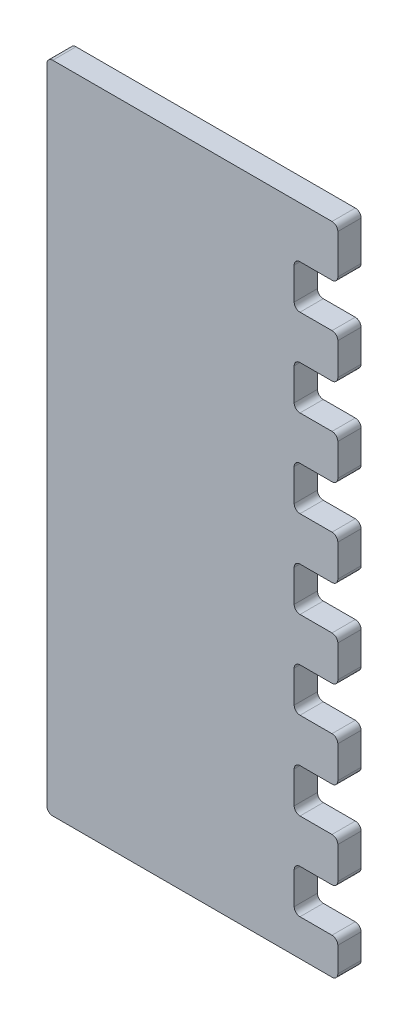
SolidWorks part; units mm, degrees
ref_plane "Front Plane" through (0, 0, 0) normal (0, 0, 1) x (1, 0, 0)
ref_plane "Top Plane" through (0, 0, 0) normal (0, 1, 0) x (1, 0, 0)
ref_plane "Right Plane" through (0, 0, 0) normal (1, 0, 0) x (0, 0, -1)
sketch "Sketch1" plane through (0, 0, 0) normal (0, 0, 1) x (1, 0, 0)
  line L1 (-100, 0) -> (100, 0)
  line L2 (-100, 0) -> (-100, 450)
  line L3 (-100, 450) -> (100, 450)
  line L4 (100, 0) -> (100, 450)
  point P4 (0, 0)
  dimension "D1" = 200
  dimension "D2" = 450
extrude "Boss-Extrude1" add sketch "Sketch1" along normal blind 16
sketch "Sketch2" plane through (0, 0, 16) normal (0, 0, 1) x (1, 0, 0)
  line L0 (100, 0) -> (100, 25)
  line L1 (100, 0) -> (100, 450) construction
  line L2 (100, 25) -> (70, 25)
  line L3 (70, 25) -> (70, 55)
  line L4 (70, 55) -> (100, 55)
  line L5 (70, 110) -> (100, 110)
  line L6 (70, 80) -> (70, 110)
  line L7 (100, 80) -> (70, 80)
  line L8 (100, 55) -> (100, 80)
  line L9 (70, 165) -> (100, 165)
  line L10 (70, 135) -> (70, 165)
  line L11 (100, 135) -> (70, 135)
  line L12 (100, 110) -> (100, 135)
  line L13 (70, 220) -> (100, 220)
  line L14 (70, 190) -> (70, 220)
  line L15 (100, 190) -> (70, 190)
  line L16 (100, 165) -> (100, 190)
  line L17 (70, 275) -> (100, 275)
  line L18 (70, 245) -> (70, 275)
  line L19 (100, 245) -> (70, 245)
  line L20 (100, 220) -> (100, 245)
  line L21 (70, 330) -> (100, 330)
  line L22 (70, 300) -> (70, 330)
  line L23 (100, 300) -> (70, 300)
  line L24 (100, 275) -> (100, 300)
  line L25 (70, 385) -> (100, 385)
  line L26 (70, 355) -> (70, 385)
  line L27 (100, 355) -> (70, 355)
  line L28 (100, 330) -> (100, 355)
  line L29 (70, 440) -> (100, 440)
  line L30 (70, 410) -> (70, 440)
  line L31 (100, 410) -> (70, 410)
  line L32 (100, 385) -> (100, 410)
  line L33 (70, 495) -> (100, 495)
  line L34 (70, 465) -> (70, 495)
  line L35 (100, 465) -> (70, 465)
  line L36 (100, 440) -> (100, 465)
  line L37 (70, 550) -> (100, 550)
  line L38 (70, 520) -> (70, 550)
  line L39 (100, 520) -> (70, 520)
  line L40 (100, 495) -> (100, 520)
  line L41 (70, 605) -> (100, 605)
  line L42 (70, 575) -> (70, 605)
  line L43 (100, 575) -> (70, 575)
  line L44 (100, 550) -> (100, 575)
  line L45 (70, 660) -> (100, 660)
  line L46 (70, 630) -> (70, 660)
  line L47 (100, 630) -> (70, 630)
  line L48 (100, 605) -> (100, 630)
  line L49 (70, 715) -> (100, 715)
  line L50 (70, 685) -> (70, 715)
  line L51 (100, 685) -> (70, 685)
  line L52 (100, 660) -> (100, 685)
  line M3 (100, 0) -> (100, 450)
  dimension "D1" = 25
  dimension "D2" = 30
  dimension "D3" = 30
  dimension "D4" = 13
extrude "Cut-Extrude8" cut sketch "Sketch2" against normal through all both and the other way through all contours L4 L3 L2 M3
pattern_linear "LPattern1" count 7 spacing 60 along (0, 1, 0) of "Cut-Extrude8"
fillet "Fillet1" radius 4 32 edges at (100, 145, 8) (70, 145, 8) (70, 175, 8) (100, 175, 8) (100, 205, 8) (70, 205, 8) (70, 235, 8) (100, 235, 8) (100, 265, 8) (70, 265, 8) (70, 295, 8) (100, 295, 8) (100, 325, 8) (70, 355, 8) (100, 355, 8) (100, 385, 8) (70, 385, 8) (70, 415, 8) (100, 415, 8) (100, 450, 8) (-100, 450, 8) (-100, 0, 8) (100, 0, 8) (100, 25, 8) (70, 25, 8) (70, 55, 8) (100, 55, 8) (100, 85, 8) (70, 85, 8) (70, 115, 8) (100, 115, 8) (70, 325, 8)
